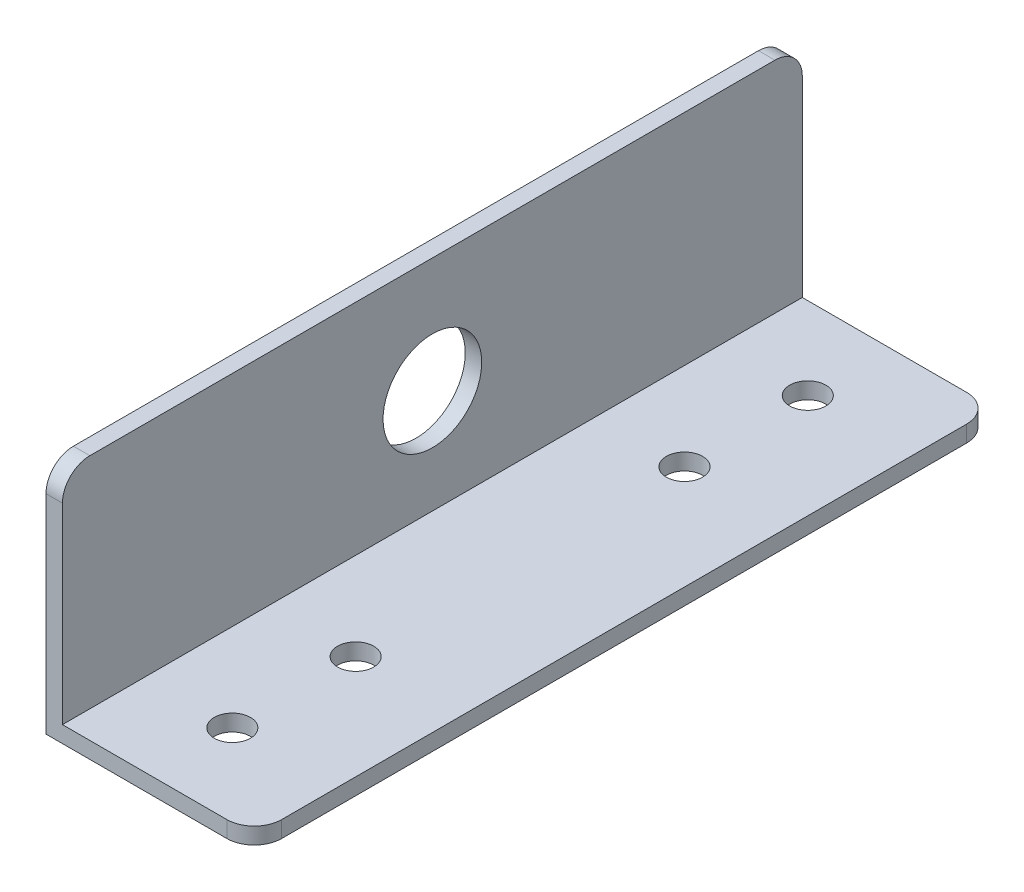
SolidWorks part; units mm, degrees
material "AISI 304"
ref_plane "Спереди" through (0, 0, 0) normal (0, 0, 1) x (1, 0, 0)
ref_plane "Сверху" through (0, 0, 0) normal (0, 1, 0) x (1, 0, 0)
ref_plane "Справа" through (0, 0, 0) normal (1, 0, 0) x (0, 0, -1)
sketch "Эскиз1" plane through (0, 0, 0) normal (0, 0, 1) x (1, 0, 0)
  line L0 (0, 0) -> (76, 0)
  line L1 (76, 0) -> (76, 6)
  line L2 (76, 6) -> (6, 6)
  line L3 (6, 6) -> (6, 86)
  line L4 (6, 86) -> (0, 86)
  line L5 (0, 86) -> (0, 0)
  dimension "D1" = 76
  dimension "D2" = 6
  dimension "D3" = 86
extrude "Бобышка-Вытянуть1" add sketch "Эскиз1" along normal mid plane 270
sketch "Эскиз3" plane through (6, 0, 0) normal (1, 0, 0) x (0, 0, -1)
  line L0 (0, 86) -> (0, 44) construction
  line L1 (-135, 86) -> (135, 86) construction
  line L2 (-135, 0) -> (135, 0) construction
  circle A0 centre (0, 44) radius 18
  dimension "D1" = 36
  dimension "D3" = 44
  dimension "D2" = 42
extrude "Вырез-Вытянуть2" cut sketch "Эскиз3" against normal through all
sketch "Эскиз4" plane through (0, 6, 0) normal (0, 1, 0) x (1, 0, 0)
  line L0 (76, -135) -> (76, 135) construction
  line L1 (0, 0) -> (76, 0) construction
  line L3 (76, 135) -> (6, 135) construction
  line L4 (38, 135) -> (38, 60) construction
  line L6 (-41.8, 0) -> (41.8, 0) construction
  circle A0 centre (38, 105) radius 6.6
  circle A1 centre (38, 60) radius 6.6
  circle A2 centre (38, -60) radius 6.6
  circle A3 centre (38, -105) radius 6.6
  dimension "D3" = 13.2
  dimension "D4" = 38
  dimension "D1" = 30
  dimension "D2" = 75
extrude "Вырез-Вытянуть3" cut sketch "Эскиз4" against normal through all
fillet "Скругление1" radius 10 4 edges at (76, 3, 135) (3, 86, 135) (3, 86, -135) (76, 3, -135)
sketch "Эскиз5" plane through (6, 0, 0) normal (1, 0, 0) x (0, 0, -1)
  circle A0 centre (0, 35) radius 18.5
  dimension "D1" = 37
split line "Разделяющая линия1" [suppressed]
sketch "Эскиз6" plane through (0, 6, 0) normal (0, 1, 0) x (1, 0, 0)
  circle A0 centre (33, 105) radius 12
  circle A1 centre (33, 60) radius 12
  circle A2 centre (33, -60) radius 12
  circle A3 centre (33, -105) radius 12
  dimension "D1" = 24
split line "Разделяющая линия2" [suppressed]
